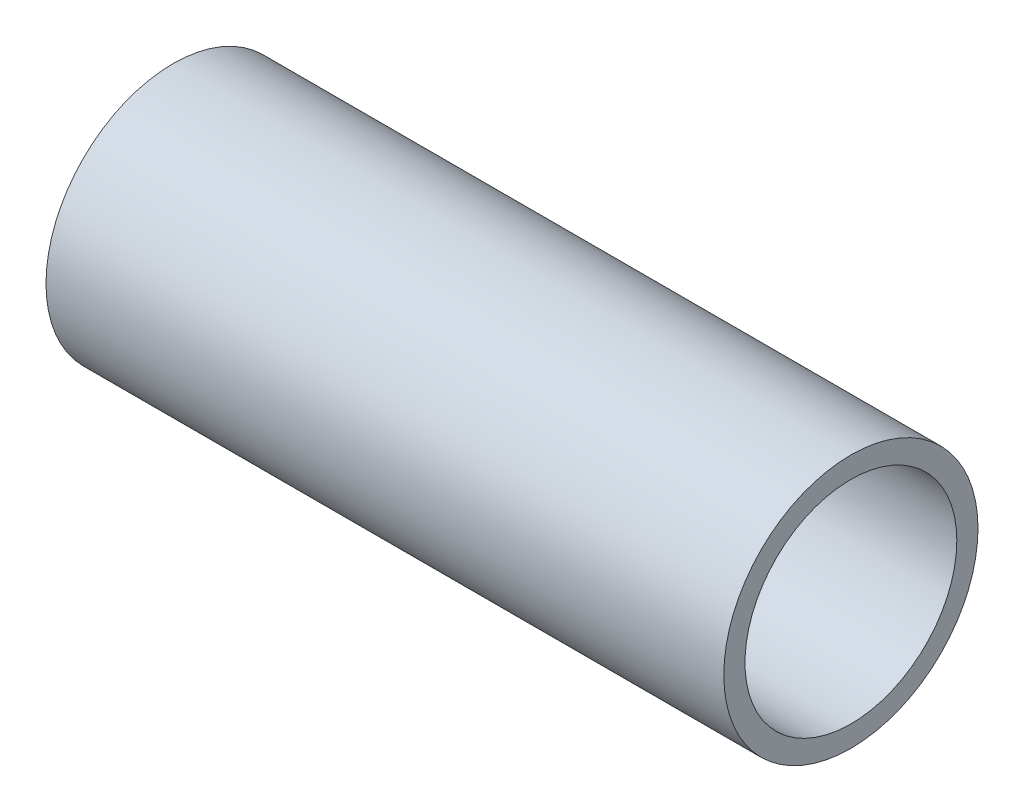
SolidWorks part; units mm, degrees
material "Alloy Steel"
ref_plane "Front Plane" through (0, 0, 0) normal (0, 0, 1) x (1, 0, 0)
ref_plane "Top Plane" through (0, 0, 0) normal (0, 1, 0) x (1, 0, 0)
ref_plane "Right Plane" through (0, 0, 0) normal (1, 0, 0) x (0, 0, -1)
sketch "Sketch1" plane through (0, 0, 0) normal (1, 0, 0) x (0, 0, -1)
  circle A0 centre (0, 0) radius 6
  circle A1 centre (0, 0) radius 5
  dimension "D1" = 12
  dimension "D2" = 1
extrude "Boss-Extrude1" add sketch "Sketch1" along normal blind 32
